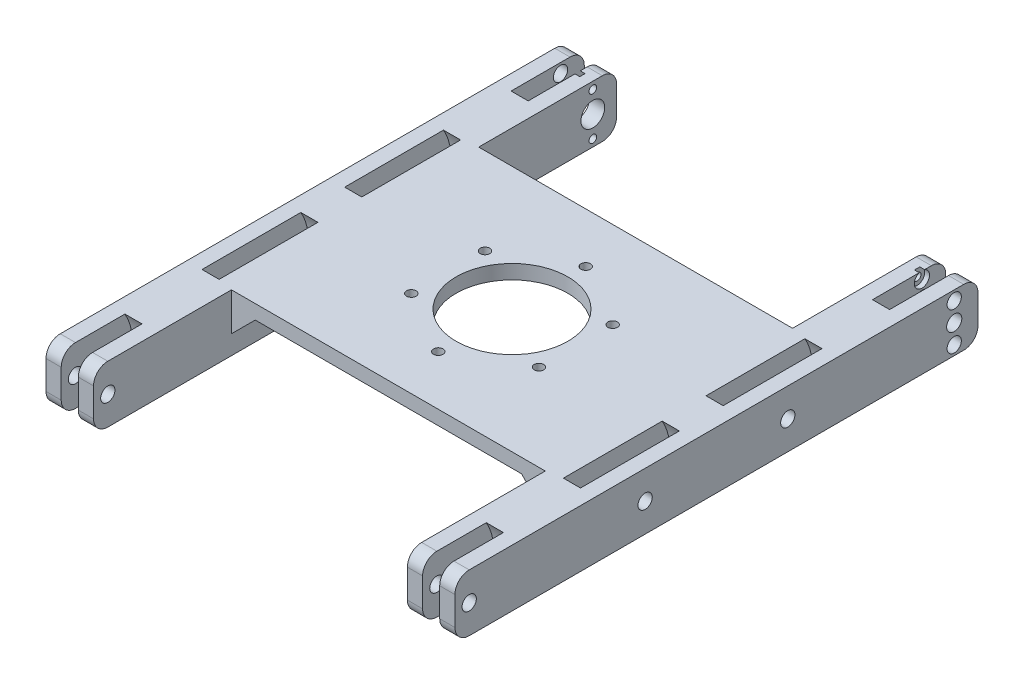
SolidWorks part; units mm, degrees
ref_plane "前视基准面" through (0, 0, 0) normal (0, 0, 1) x (1, 0, 0)
ref_plane "上视基准面" through (0, 0, 0) normal (0, 1, 0) x (1, 0, 0)
ref_plane "右视基准面" through (0, 0, 0) normal (1, 0, 0) x (0, 0, -1)
sketch "草图1" plane through (0, 0, 0) normal (0, 1, 0) x (1, 0, 0)
  line L1 (33, -26) -> (-33, -26)
  line L2 (33, -26) -> (33, 26)
  line L3 (33, 26) -> (-33, 26)
  line L4 (-33, -26) -> (-33, 26)
  line L5 (0, 26) -> (0, -26) construction
  line L6 (33, 0) -> (-33, 0) construction
  point P0 (0, 0)
  dimension "D1" = 66
  dimension "D2" = 52
extrude "凸台-拉伸1" add sketch "草图1" along normal blind 3
sketch "草图2" plane through (-33, 0, 0) normal (-1, 0, 0) x (0, 0, 1)
  line L0 (-26, 3) -> (26, 3) construction
  line L1 (-55, 3) -> (55, 3)
  line L2 (-55, 3) -> (-55, -9)
  line L3 (-55, -9) -> (55, -9)
  line L4 (55, 3) -> (55, -9)
  line L6 (0, 0) -> (0, -9) construction
  line L7 (-26, 0) -> (26, 0) construction
  dimension "D1" = 12
  dimension "D2" = 110
extrude "凸台-拉伸2" add sketch "草图2" along normal blind 10
sketch "草图4" plane through (-43, 0, 0) normal (-1, 0, 0) x (0, 0, 1)
  line L0 (-55, -3) -> (55, -3) construction
  line L1 (-55, 3) -> (-55, -9) construction
  line L2 (55, -9) -> (55, 3) construction
  line L3 (0, 3) -> (0, -9) construction
  line L4 (55, 3) -> (-55, 3) construction
  line L5 (-55, -9) -> (55, -9) construction
  circle A0 centre (-50, -3) radius 1.6
  circle A1 centre (52, -3) radius 1.5
  circle A2 centre (-15, -3) radius 1.5
  circle A3 centre (15, -3) radius 1.5
  dimension "D1" = 3.2
  dimension "D2" = 3
  dimension "D3" = 5
  dimension "D4" = 3
  dimension "D5" = 30
  dimension "D6" = 15
extrude "切除-拉伸1" cut sketch "草图4" against normal up to next
ref_plane "基准面1" through (-38, 0, 0) normal (1, 0, 0) x (0, 0, -1)
sketch "草图8" plane through (-38, 0, 0) normal (1, 0, 0) x (0, 0, -1)
  line L0 (-27, -3) -> (-27, -9)
  line L1 (55, -9) -> (-55, -9) construction
  line L2 (-3, -3) -> (-3, -9)
  line L3 (-3, -9) -> (-27, -9)
  line L4 (3, -3) -> (3, -9)
  line L5 (3, -9) -> (27, -9)
  line L6 (27, -9) -> (27, -3)
  circle A0 centre (-52, -3) radius 12
  arc A2 (27, -3) -> (3, -3) centre (15, -3) ccw
  circle A3 centre (50, -3) radius 12
  arc A4 (-3, -3) -> (-27, -3) centre (-15, -3) ccw
  dimension "D1" = 24
extrude "切除-拉伸4" cut sketch "草图8" against normal blind 1.8 and the other way blind 1.8
sketch "草图5" plane through (-33, 0, 0) normal (-1, 0, 0) x (0, 0, 1)
  line L0 (-50, 1.5) -> (-50, -3) construction
  line L1 (-50, -7.5) -> (-50, -3) construction
  circle A0 centre (-50, 1.5) radius 0.8
  circle A1 centre (-50, -7.5) radius 0.8
  circle A2 centre (-50, -3) radius 2.5
  dimension "D2" = 1.6
  dimension "D4" = 5
  dimension "D1" = 9
  dimension "D3" = 4.5
extrude "切除-拉伸2" cut sketch "草图5" along normal up to next
sketch "草图10" plane through (-43, 0, 0) normal (-1, 0, 0) x (0, 0, 1)
  line L0 (-50, -3) -> (-50, -12.2714) construction
  line L1 (-50, -3) -> (-50, 5.0153) construction
  circle A0 centre (-50, -7) radius 1.5
  circle A1 centre (-50, 1) radius 1.5
  dimension "D1" = 8
  dimension "D2" = 3
  dimension "D3" = 4
extrude "切除-拉伸5" cut sketch "草图10" against normal up to next contours A0 | A1
sketch "草图11" plane through (-36.2, 0, 0) normal (-1, 0, 0) x (0, 0, 1)
  circle A0 centre (-50, 1.5) radius 1.6
  circle A1 centre (-50, -7.5) radius 1.6
  dimension "D1" = 3.2
  dimension "D2" = 3.2
extrude "切除-拉伸6" cut sketch "草图11" against normal blind 1
mirror "镜向1" about plane through (0, 0, 0) normal (1, 0, 0) of "切除-拉伸6", "切除-拉伸2", "切除-拉伸1", "凸台-拉伸2", "切除-拉伸4", "切除-拉伸5"
fillet "圆角1" radius 3 16 edges at (-41.4, 3, -55) (-41.4, -9, -55) (-41.4, -9, 55) (-41.4, 3, 55) (41.4, -9, -55) (41.4, 3, -55) (41.4, 3, 55) (41.4, -9, 55) (34.6, -9, 55) (34.6, 3, 55) (34.6, -9, -55) (34.6, 3, -55) (-34.6, 3, 55) (-34.6, -9, 55) (-34.6, -9, -55) (-34.6, 3, -55)
sketch "草图6" plane through (0, 3, 0) normal (0, 1, 0) x (1, 0, 0)
  line L0 (0, 15.5) -> (0, 0) construction
  circle A0 centre (0, 15.5) radius 1
  circle A4 centre (0, 0) radius 11.75
  point P0 (0, 0)
  dimension "D2" = 15.5
  dimension "D3" = 23.5
  dimension "D1" = 2
extrude "切除-拉伸3" cut sketch "草图6" against normal up to next
pattern_circular "阵列(圆周)1" count 6 over 360 about axis through (0, 0, 0) along (0, 1, 0) of "切除-拉伸3"
sketch "草图9" plane through (0, 0, -26) normal (0, 0, -1) x (-1, 0, 0)
  line L0 (33, 0) -> (28, 0)
  line L1 (-33, 0) -> (33, 0) construction
  line L2 (28, 0) -> (33, -5)
  line L3 (33, 0) -> (33, -6) construction
  line L4 (33, -5) -> (33, 0)
  dimension "D1" = 45
  dimension "D2" = 5
extrude "凸台-拉伸3" add sketch "草图9" against normal blind 5
pattern_linear "阵列(线性)1" count 4 spacing 15.6667 along (0, 0, 1) of "凸台-拉伸3"
mirror "镜向2" about plane through (0, 0, 0) normal (1, 0, 0) of "阵列(线性)1", "凸台-拉伸3"
